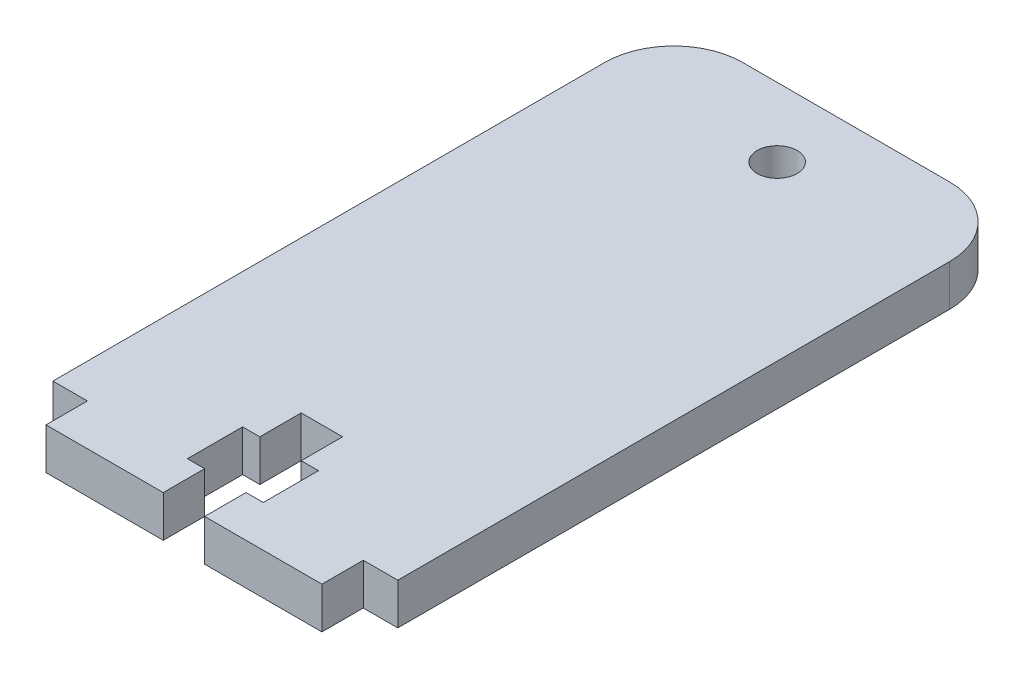
SolidWorks part; units mm, degrees
ref_plane "前视基准面" through (0, 0, 0) normal (0, 0, 1) x (1, 0, 0)
ref_plane "上视基准面" through (0, 0, 0) normal (0, 1, 0) x (1, 0, 0)
ref_plane "右视基准面" through (0, 0, 0) normal (1, 0, 0) x (0, 0, -1)
other "Configuration Table"
sketch "草图1" plane through (0, 0, 0) normal (0, 1, 0) x (1, 0, 0)
  line L1 (5, 0) -> (20, 0)
  line L2 (0, -5) -> (0, -45)
  line L3 (0, -45) -> (25, -45)
  line L4 (25, -5) -> (25, -45)
  line L5 (2.5, -45) -> (22.5, -45)
  line L6 (2.5, -45) -> (2.5, -48)
  line L7 (2.5, -48) -> (22.5, -48)
  line L8 (22.5, -45) -> (22.5, -48)
  line L9 (11, -48) -> (14, -48)
  line L10 (11, -48) -> (11, -38)
  line L11 (11, -38) -> (14, -38)
  line L12 (14, -48) -> (14, -38)
  line L13 (9.75, -41) -> (15.25, -41)
  line L14 (9.75, -41) -> (9.75, -45)
  line L15 (9.75, -45) -> (15.25, -45)
  line L16 (15.25, -41) -> (15.25, -45)
  line L17 (9.75, -41) -> (15.25, -45) construction
  line L18 (9.75, -45) -> (15.25, -41) construction
  circle A0 centre (12.5, -5) radius 1.45
  arc A1 (25, -5) -> (20, 0) centre (20, -5) ccw
  arc A2 (5, 0) -> (0, -5) centre (5, -5) ccw
  point P13 (25, 0)
  point P16 (0, 0)
  point P21 (12.5, -43)
  dimension "D6" = 2.9
  dimension "D7" = 5
  dimension "D8" = 5
  dimension "D1" = 25
  dimension "D2" = 45
  dimension "D3" = 20
  dimension "D4" = 3
  dimension "D5" = 2.5
  dimension "D9" = 3
  dimension "D10" = 10
  dimension "D11" = 8.5
  dimension "D12" = 5.5
  dimension "D13" = 4
  dimension "D14" = 3
  dimension "D15" = 1.25
extrude "凸台-拉伸1" add sketch "草图1" along normal blind 3 contours L1 A2 L2 L3 L14 L13 L10 L11 L12 L16 L5 L4 A1 A0 | L12 L7 L8 L5 L3 | L7 L10 L5 L3 L6
